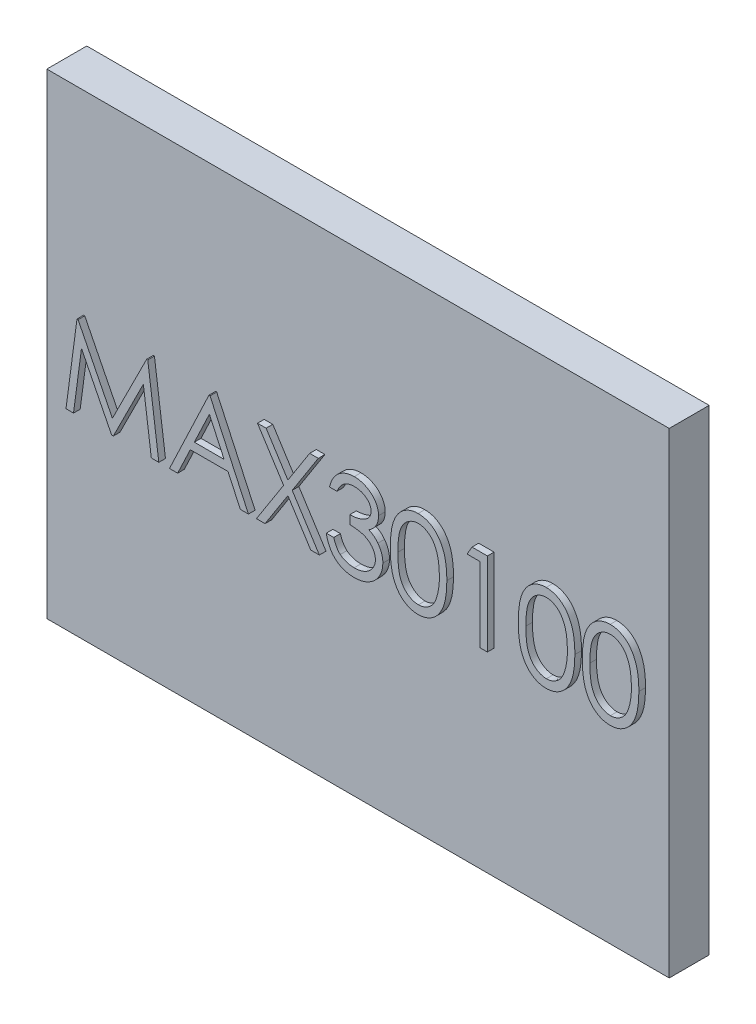
SolidWorks part; units mm, degrees
ref_plane "Front Plane" through (0, 0, 0) normal (0, 0, 1) x (1, 0, 0)
ref_plane "Top Plane" through (0, 0, 0) normal (0, 1, 0) x (1, 0, 0)
ref_plane "Right Plane" through (0, 0, 0) normal (1, 0, 0) x (0, 0, -1)
sketch "Sketch1" plane through (0, 0, 0) normal (0, 0, 1) x (1, 0, 0)
  line L1 (-9.35, 7.15) -> (9.35, 7.15)
  line L2 (-9.35, 7.15) -> (-9.35, -7.15)
  line L3 (-9.35, -7.15) -> (9.35, -7.15)
  line L4 (9.35, 7.15) -> (9.35, -7.15)
  line L5 (-9.35, 7.15) -> (9.35, -7.15) construction
  line L6 (-9.35, -7.15) -> (9.35, 7.15) construction
  point P0 (0, 0)
  dimension "D1" = 14.3
  dimension "D2" = 18.7
extrude "Boss-Extrude1" add sketch "Sketch1" along normal blind 1.2
sketch "Sketch2" plane through (0, 0, 1.2) normal (0, 0, 1) x (1, 0, 0)
  line L0 (-9.35, -1.2) -> (9.35, -1.2) construction
  line L1 (-9.35, 7.15) -> (-9.35, -7.15) construction
  line L2 (9.35, -7.15) -> (9.35, 7.15) construction
  text T0 "MAX30100" font "Century Gothic" height 2.5
  dimension "D1" = 1.2
extrude "Boss-Extrude2" add sketch "Sketch2" along normal blind 0.2
